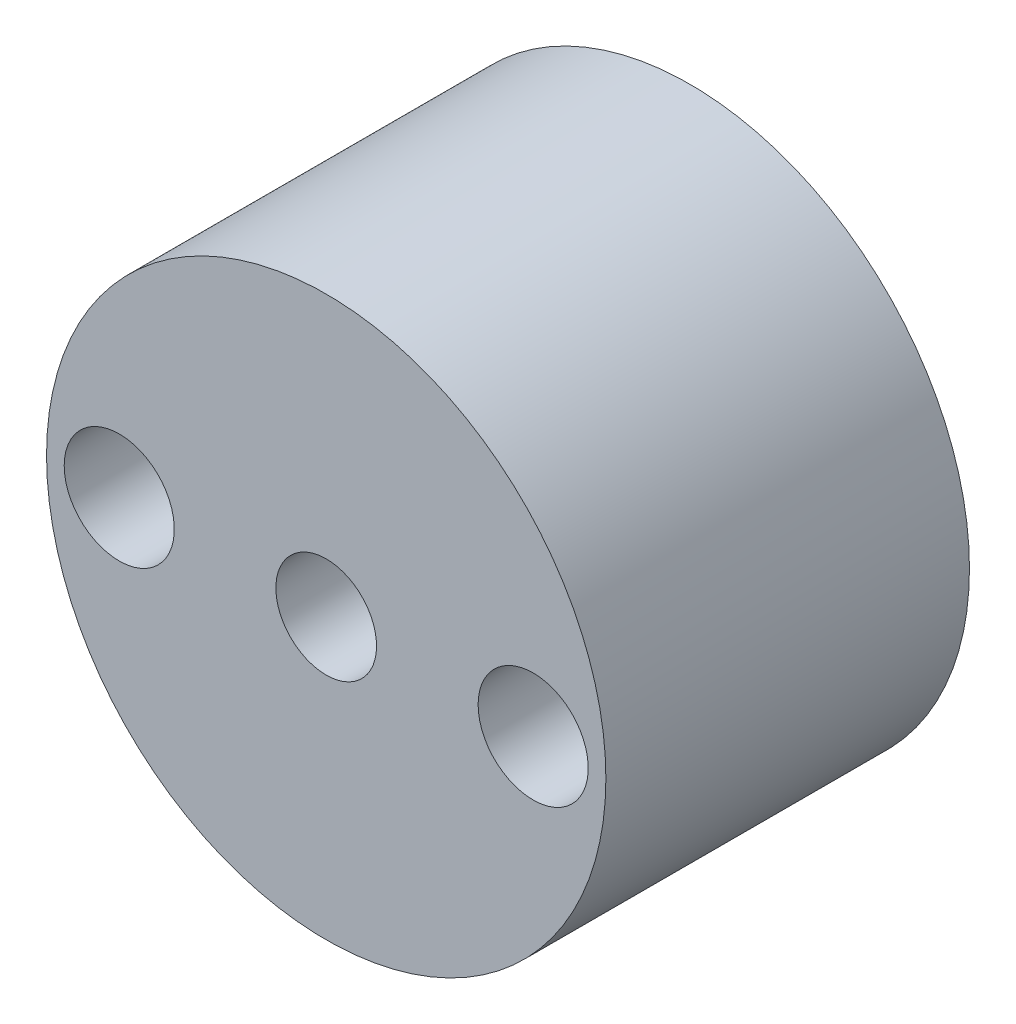
SolidWorks part; units mm, degrees
ref_plane "Front Plane" through (0, 0, 0) normal (0, 0, 1) x (1, 0, 0)
ref_plane "Top Plane" through (0, 0, 0) normal (0, 1, 0) x (1, 0, 0)
ref_plane "Right Plane" through (0, 0, 0) normal (1, 0, 0) x (0, 0, -1)
sketch "Sketch1" plane through (0, 0, 0) normal (0, 0, 1) x (1, 0, 0)
  line L0 (-2.413, 0) -> (2.413, 0) construction
  line L1 (-2.413, -2.54) -> (0, 0) construction
  line L2 (-2.413, -2.54) -> (-2.413, 2.54)
  line L3 (-2.413, 2.54) -> (2.413, 2.54) construction
  line L4 (2.413, -2.54) -> (2.413, 2.54)
  line L5 (0, 0) -> (2.413, 2.54) construction
  line L6 (-2.413, 2.54) -> (0, 0) construction
  line L7 (0, 0) -> (2.413, -2.54) construction
  line L8 (-2.413, -2.54) -> (2.413, -2.54) construction
  arc A0 (-2.413, 2.54) -> (2.413, 2.54) centre (0, 0) cw
  arc A1 (-2.413, -2.54) -> (2.413, -2.54) centre (0, 0) ccw
  circle A2 centre (0, 0) radius 6.35
  point P0 (0, 0)
  dimension "D3" = 12.7
  dimension "D1" = 4.826
  dimension "D2" = 2.54
extrude "Boss-Extrude1" add sketch "Sketch1" along normal blind 5.08
sketch "Sketch2" plane through (0, 0, 5.08) normal (0, 0, 1) x (1, 0, 0)
  circle A0 centre (0, 0) radius 1.143
  circle A1 centre (0, 0) radius 6.35
  dimension "D1" = 12.7
  dimension "D2" = 2.286
extrude "Boss-Extrude2" add sketch "Sketch2" along normal blind 3.175
hole_wizard "Tap Drill for M3 Tap2" positions "Sketch7" profile "Sketch6" hole size "M3" standard "ISO" end condition through all
sketch "Sketch7" plane through (0, 0, 0) normal (0, 0, -1) x (-1, 0, 0)
  line L0 (-6.35, 0) -> (6.35, 0) construction
  line L1 (-2.413, -2.54) -> (-2.413, 2.54) construction
  line L2 (2.413, 2.54) -> (2.413, -2.54) construction
  circle A0 centre (0, 0) radius 6.35 construction
  point P0 (-4.699, 0)
  point P2 (4.699, 0)
  dimension "D1" = 2.286
  dimension "D2" = 2.286
sketch "Sketch6" plane through (4.699, 0, 0) normal (1, 0, 0) x (0, 1, 0)
  line L0 (0, 0) -> (0, 8.255)
  line L1 (0, 8.255) -> (1.25, 8.255)
  line L2 (1.25, 8.255) -> (1.25, 0)
  line L5 (1.25, 0) -> (0, 0)
  line L11 (0, -6.35) -> (0, 107.95) construction
  dimension "Thru Hole Dia." = 2.5
  dimension "Thru Hole Depth" = 8.255
